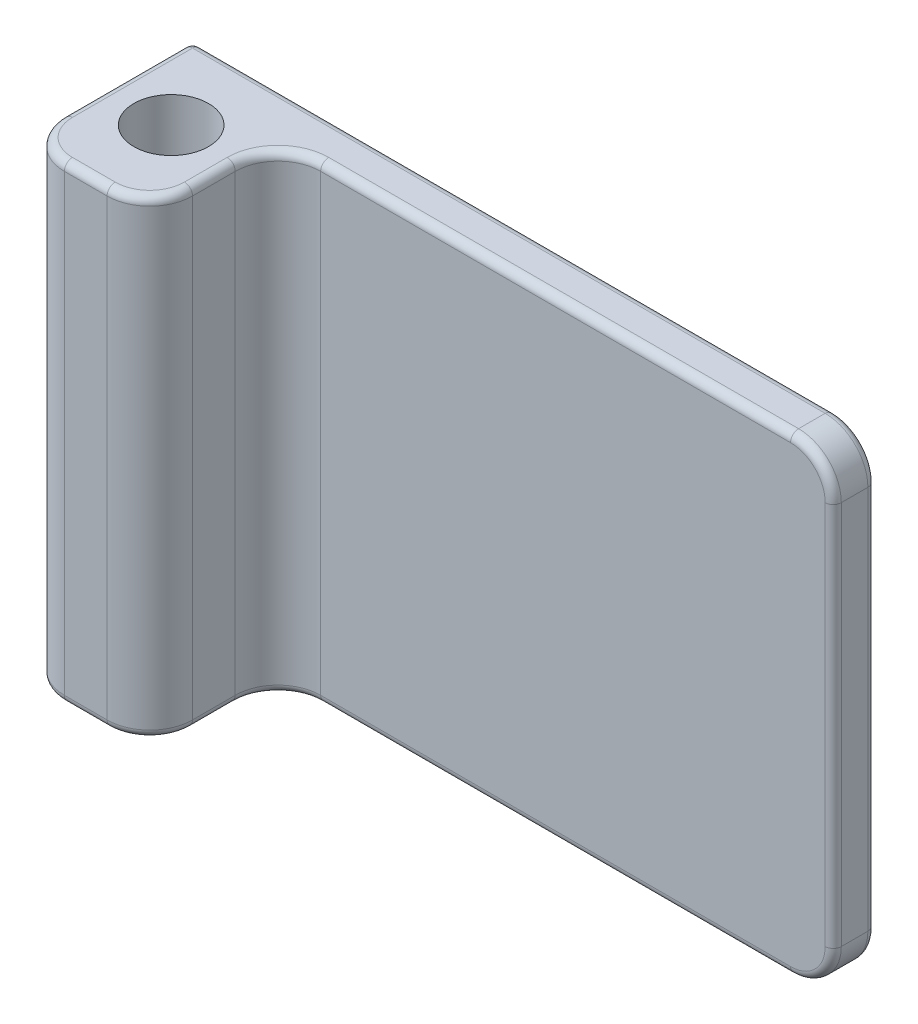
SolidWorks part; units mm, degrees
ref_plane "Alzado" through (0, 0, 0) normal (0, 0, 1) x (1, 0, 0)
ref_plane "Planta" through (0, 0, 0) normal (0, 1, 0) x (1, 0, 0)
ref_plane "Vista lateral" through (0, 0, 0) normal (1, 0, 0) x (0, 0, -1)
sketch "Croquis1" plane through (0, 0, 0) normal (0, 0, 1) x (1, 0, 0)
  line L1 (-101.6, 69.85) -> (101.6, 69.85)
  line L2 (-101.6, 69.85) -> (-101.6, -69.85)
  line L3 (-101.6, -69.85) -> (101.6, -69.85)
  line L4 (101.6, 69.85) -> (101.6, -69.85)
  line L5 (-101.6, 69.85) -> (101.6, -69.85) construction
  line L6 (-101.6, -69.85) -> (101.6, 69.85) construction
  point P0 (0, 0)
  dimension "D1" = 139.7
  dimension "D2" = 203.2
extrude "Saliente-Extruir1" add sketch "Croquis1" along normal blind 50.8
sketch "Croquis2" plane through (0, -69.85, 0) normal (0, -1, 0) x (1, 0, 0)
  line L0 (-101.6, 50.8) -> (101.6, 50.8) construction
  line L1 (-63.5, 50.8) -> (101.6, 50.8)
  line L2 (-63.5, 50.8) -> (-63.5, 12.7)
  line L3 (-63.5, 12.7) -> (101.6, 12.7)
  line L4 (101.6, 50.8) -> (101.6, 12.7)
  line L5 (101.6, 50.8) -> (101.6, 0) construction
  line L6 (-101.6, 0) -> (101.6, 0) construction
  line L7 (-101.6, 50.8) -> (-101.6, 0) construction
  dimension "D1" = 12.7
  dimension "D2" = 38.1
extrude "Cortar-Extruir1" cut sketch "Croquis2" against normal through all
sketch "Croquis3" plane through (0, -69.85, 0) normal (0, -1, 0) x (1, 0, 0)
  line L0 (-82.55, 50.8) -> (-82.55, 0) construction
  line L1 (-101.6, 50.8) -> (-63.5, 50.8) construction
  line L2 (-101.6, 0) -> (101.6, 0) construction
  circle A0 centre (-82.55, 25.4) radius 11.1125
  dimension "D1" = 22.225
extrude "Cortar-Extruir2" cut sketch "Croquis3" against normal through all
fillet "Redondeo1" radius 12.7 3 edges at (-101.6, 0, 50.8) (-63.5, 0, 50.8) (-63.5, 0, 12.7)
fillet "Redondeo2" radius 12.7 2 edges at (101.6, 69.85, 6.35) (101.6, -69.85, 6.35)
fillet "Redondeo3" radius 2.4 23 edges at (-6.35, 69.85, 0) (97.8803, 66.1303, 0) (101.6, 0, 0) (97.8803, -66.1303, 0) (-101.6, -69.85, 19.05) (-97.8803, -69.85, 47.0803) (-82.55, -69.85, 50.8) (-67.2197, -69.85, 47.0803) (-63.5, -69.85, 31.75) (-59.7803, -69.85, 16.4197) (-101.6, 69.85, 19.05) (-97.8803, 69.85, 47.0803) (-82.55, 69.85, 50.8) (-67.2197, 69.85, 47.0803) (-63.5, 69.85, 31.75) (-59.7803, 69.85, 16.4197) (19.05, 69.85, 12.7) (97.8803, 66.1303, 12.7) (101.6, 0, 12.7) (97.8803, -66.1303, 12.7) (-101.6, 0, 0) (-6.35, -69.85, 0) (19.05, -69.85, 12.7)
